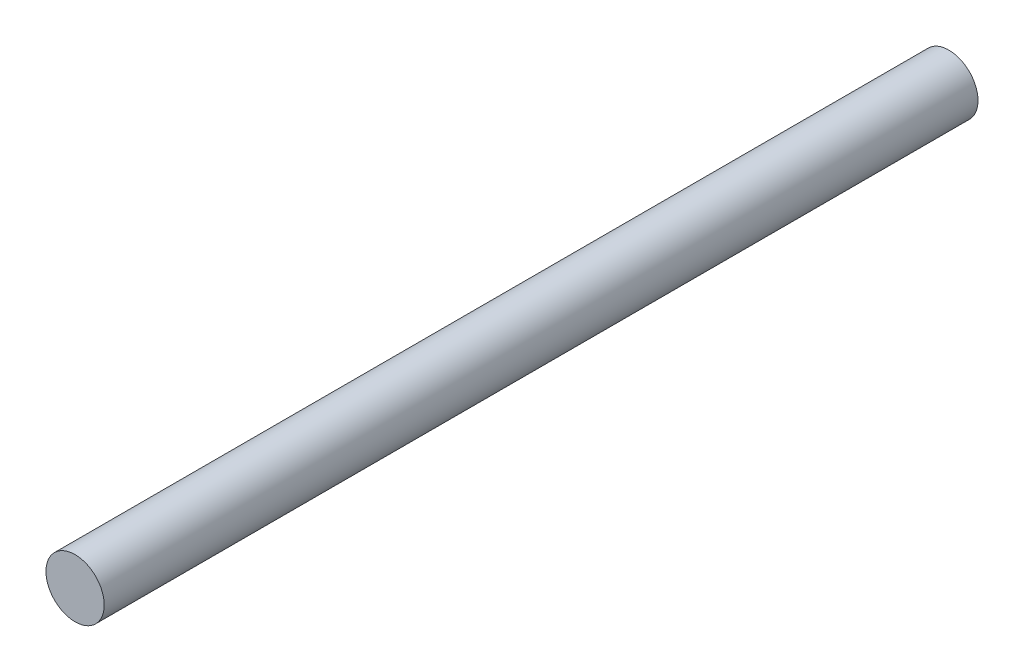
SolidWorks part; units mm, degrees
ref_plane "Front Plane" through (0, 0, 0) normal (0, 0, 1) x (1, 0, 0)
ref_plane "Top Plane" through (0, 0, 0) normal (0, 1, 0) x (1, 0, 0)
ref_plane "Right Plane" through (0, 0, 0) normal (1, 0, 0) x (0, 0, -1)
sketch "Sketch1" plane through (0, 0, 0) normal (0, 0, 1) x (1, 0, 0)
  circle A0 centre (0, 0) radius 4
  dimension "D1" = 8
extrude "Boss-Extrude1" add sketch "Sketch1" along normal blind 120
sketch "Sketch4" plane through (0, 0, 120) normal (0, 0, 1) x (1, 0, 0)
  spline S0 degree 2 poles (-4, 0) (-15.5028, 11.1791) (-24.5, 24.5) knots 0 0 0 1 1 1
  point P2 (-24.5, 9.8798)
  point P4 (-14.0339, 0.3778)
  point P5 (-24.5, 9.4077)
  point P7 (-17.0438, 6.2206)
  point P8 (-13.0571, 9.1683)
  point P9 (-12.7635, 9.2427)
  dimension "D1" = 24.5
  dimension "D2" = 24.5
sketch "Sketch6" plane through (0, 0, 120) normal (0, 0, 1) x (1, 0, 0)
  circle A0 centre (0, 0) radius 4
curve "Helix/Spiral2" pitch 20 height 120 turns 6
